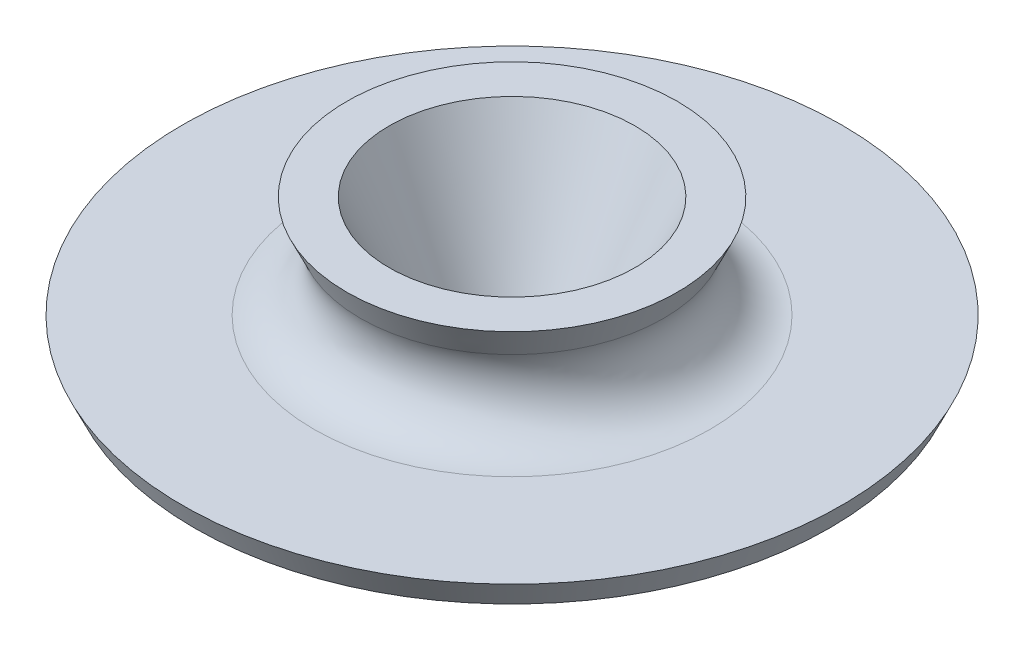
SolidWorks part; units mm, degrees
ref_plane "Front Plane" through (0, 0, 0) normal (0, 0, 1) x (1, 0, 0)
ref_plane "Top Plane" through (0, 0, 0) normal (0, 1, 0) x (1, 0, 0)
ref_plane "Right Plane" through (0, 0, 0) normal (1, 0, 0) x (0, 0, -1)
sketch "Sketch1" plane through (0, 0, 0) normal (0, 0, 1) x (1, 0, 0)
  line L0 (0, 0) -> (0, 64.3123) construction
  line L1 (-12.7, 0) -> (-19.7064, 0)
  line L2 (-19.7064, 0) -> (-22.6675, 6.35)
  line L3 (-22.6675, 6.35) -> (-78.7191, 6.35)
  line L4 (-78.7191, 6.35) -> (-81.6802, 12.7)
  line L5 (-81.6802, 12.7) -> (-29.1318, 12.7)
  line L6 (-29.1318, 12.7) -> (-40.976, 38.1)
  line L7 (-40.976, 38.1) -> (-30.4663, 38.1)
  line L8 (-30.4663, 38.1) -> (-12.7, 0)
  dimension "D1" = 38.1
  dimension "D2" = 6.35
  dimension "D3" = 9.525
  dimension ".25" = 6.35
  dimension "D4" = 6.35
  dimension "D5" = 25.4
  dimension "D6" = 57.15
  dimension "D7" = 25
revolve "Revolve1" add sketch "Sketch1" angle 360 about L0
fillet "Fillet1" radius 12.7 1 edges at (0, 12.7, -29.1318)
